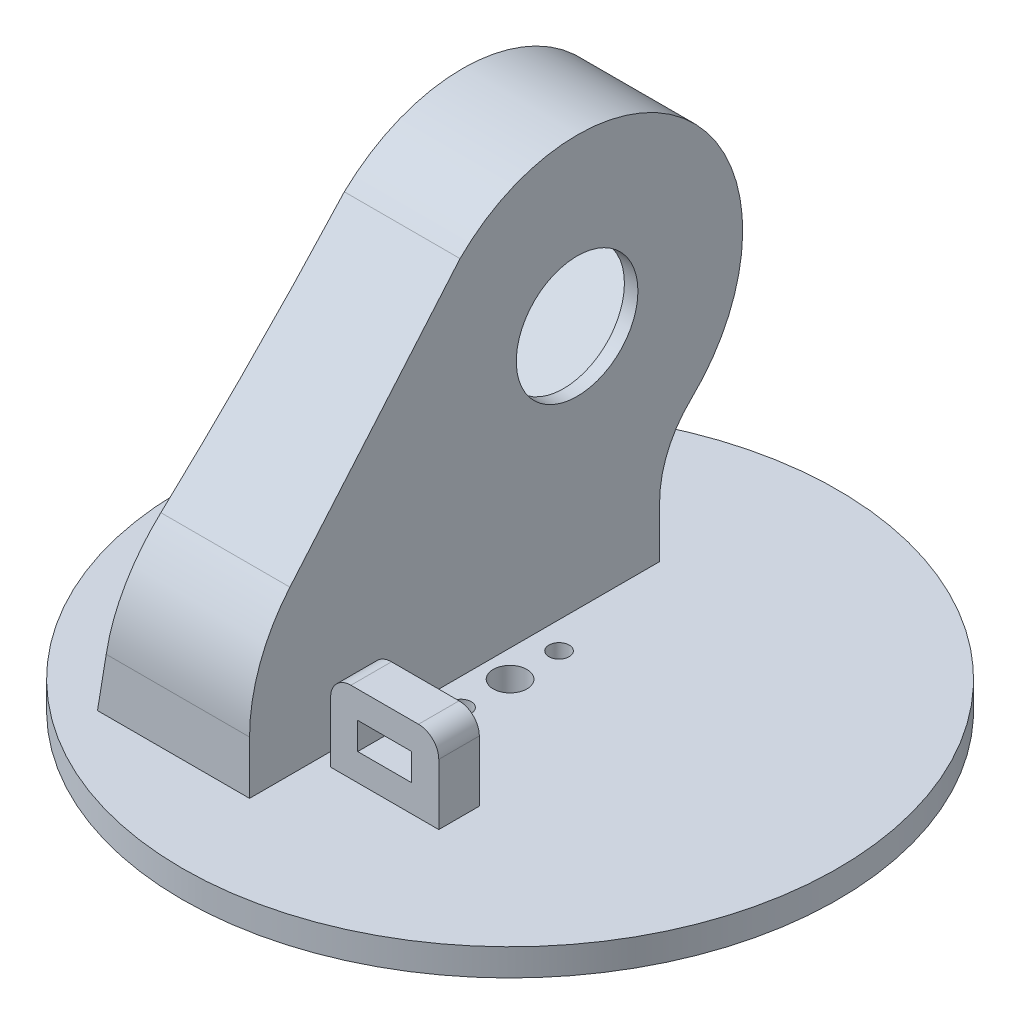
SolidWorks part; units mm, degrees
ref_plane "Front Plane" through (0, 0, 0) normal (0, 0, 1) x (1, 0, 0)
ref_plane "Top Plane" through (0, 0, 0) normal (0, 1, 0) x (1, 0, 0)
ref_plane "Right Plane" through (0, 0, 0) normal (1, 0, 0) x (0, 0, -1)
sketch "Sketch2" plane through (0, 0, 0) normal (0, 1, 0) x (1, 0, 0)
  circle A0 centre (0, 0) radius 48.5
  dimension "D1" = 97
extrude "Boss-Extrude1" add sketch "Sketch2" along normal blind 4
sketch "Sketch4" plane through (0, 0, 0) normal (0, -1, 0) x (1, 0, 0)
  circle A0 centre (0, 7.25) radius 1.5
  circle A1 centre (0, -7.25) radius 1.5
  dimension "D1" = 3
  dimension "D2" = 3
  dimension "D3" = 14.5
  dimension "D4" = 7.25
extrude "Cut-Extrude2" cut sketch "Sketch4" against normal through all
sketch "Sketch5" plane through (0, 0, 0) normal (0, -1, 0) x (1, 0, 0)
  circle A0 centre (0, 0) radius 2.5
  point P3 (0, 0)
  dimension "D1" = 5
extrude "Cut-Extrude3" cut sketch "Sketch5" against normal through all
ref_plane "Plane1" through (-4, 0, 0) normal (1, 0, 0) x (0, 0, -1)
sketch "Sketch7" plane through (-4, 0, 0) normal (1, 0, 0) x (0, 0, -1)
  line L0 (23.1299, 11.6445) -> (23.1299, 4)
  line L5 (48.5, 4) -> (-48.5, 4) construction
  line L6 (-27.2273, 29.5362) -> (-1.2843, 55.4793)
  line L7 (-43.5609, 4) -> (23.1299, 4)
  line L11 (-34.5496, 4) -> (-34.5496, 11.8586)
  arc A4 (28.7298, 24.692) -> (-1.2843, 55.4793) centre (13.9185, 40.2765) ccw
  arc A5 (28.7298, 24.692) -> (23.1299, 11.6445) centre (41.1299, 11.6445) ccw
  arc A6 (-27.2273, 29.5362) -> (-34.5496, 11.8586) centre (-9.5496, 11.8586) ccw
  dimension "D1" = 25
  dimension "D4" = 43
  dimension "D3" = 18
  dimension "D5" = 45
extrude "Boss-Extrude2" add sketch "Sketch7" against normal blind 14
ref_plane "Plane2" through (-6, 0, 0) normal (1, 0, 0) x (0, 0, -1)
sketch "Sketch8" plane through (-6, 0, 0) normal (1, 0, 0) x (0, 0, -1)
  line L0 (-27.2273, 29.5362) -> (-1.2843, 55.4793) construction
  line L1 (-15.2496, 25.9576) -> (13.7417, 54.9489)
  line L2 (-15.2496, 25.9576) -> (-0.4004, 11.1083)
  line L3 (-0.4004, 11.1083) -> (28.591, 40.0997)
  line L4 (13.7417, 54.9489) -> (28.591, 40.0997)
  line L5 (-15.2496, 25.9576) -> (28.591, 40.0997) construction
  line L6 (-0.4004, 11.1083) -> (13.7417, 54.9489) construction
  point P0 (6.6707, 33.0286)
  point P11 (13.9185, 40.2765)
  dimension "D1" = 41
  dimension "D2" = 21
  dimension "D3" = 90
  dimension "D4" = 20.5
  dimension "D5" = 90
  dimension "D6" = 10.25
  dimension "D7" = 10.5
extrude "Cut-Extrude5" cut sketch "Sketch8" against normal up to next
sketch "Sketch9" plane through (-18, 0, 0) normal (-1, 0, 0) x (0, 0, 1)
  line L0 (-13.7417, 54.9489) -> (-28.591, 40.0997) construction
  line L3 (-21.1664, 47.5243) -> (-22.536, 48.894) construction
  circle A0 centre (-20.1057, 53.5347) radius 1.3
  circle A1 centre (-27.1768, 46.4637) radius 1.3
  circle A2 centre (6.7644, 12.5225) radius 1.3
  circle A3 centre (13.8354, 19.5936) radius 1.3
  dimension "D1" = 2.6
  dimension "D5" = 5
  dimension "D6" = 90
  dimension "D2" = 3.5
  dimension "D3" = 2
  dimension "D4" = 2
extrude "Cut-Extrude6" cut sketch "Sketch9" against normal blind 7.5
sketch "Sketch11" plane through (-4, 0, 0) normal (1, 0, 0) x (0, 0, -1)
  circle A0 centre (13.9185, 40.2765) radius 9
  dimension "D1" = 18
extrude "Cut-Extrude9" cut sketch "Sketch11" against normal up to next
sketch "Sketch17" plane through (-18, 0, 0) normal (-1, 0, 0) x (0, 0, 1)
  line L0 (29.3486, 31.6576) -> (3.4056, 57.6006)
  line L1 (-26.1299, 11.6445) -> (-26.1299, 1)
  line L2 (-26.1299, 1) -> (37.5496, 1)
  line L3 (37.5496, 1) -> (37.5496, 11.8586)
  line L4 (27.2273, 29.5362) -> (1.2843, 55.4793)
  line L5 (-23.1299, 11.6445) -> (-23.1299, 4)
  line L6 (-23.1299, 4) -> (34.5496, 4)
  line L7 (34.5496, 4) -> (34.5496, 11.8586)
  line L9 (-23.1299, 11.6445) -> (-23.1299, 4)
  line L10 (-23.1299, 4) -> (34.5496, 4)
  line L11 (34.5496, 4) -> (34.5496, 11.8586)
  line L12 (-26.1299, 4) -> (37.5496, 4)
  line L13 (48.5, 4) -> (-48.5, 4) construction
  line L14 (3.4056, 57.6006) -> (28.5745, 28.0776)
  line L15 (1.2843, 55.4793) -> (26.295, 26.1272)
  line L16 (31.5496, 11.8586) -> (31.5496, 4)
  line L18 (27.2273, 29.5362) -> (1.2843, 55.4793) construction
  arc A0 (3.4056, 57.6006) -> (-30.7965, 22.5174) centre (-13.9185, 40.2765) ccw
  arc A1 (-26.1299, 11.6445) -> (-30.7965, 22.5174) centre (-41.1299, 11.6445) ccw
  arc A2 (37.5496, 11.8586) -> (29.3486, 31.6576) centre (9.5496, 11.8586) ccw
  arc A3 (1.2843, 55.4793) -> (-28.7298, 24.692) centre (-13.9185, 40.2765) ccw
  arc A4 (-23.1299, 11.6445) -> (-28.7298, 24.692) centre (-41.1299, 11.6445) ccw
  arc A5 (34.5496, 11.8586) -> (27.2273, 29.5362) centre (9.5496, 11.8586) ccw
  arc A6 (1.2843, 55.4793) -> (-28.7298, 24.692) centre (-13.9185, 40.2765) ccw
  arc A7 (-23.1299, 11.6445) -> (-28.7298, 24.692) centre (-41.1299, 11.6445) ccw
  arc A8 (34.5496, 11.8586) -> (27.2273, 29.5362) centre (9.5496, 11.8586) ccw
  arc A9 (31.5496, 11.8586) -> (25.106, 27.4149) centre (9.5496, 11.8586) ccw
  line M16 (27.2273, 29.5362) -> (1.2843, 55.4793)
  arc M17 (1.2843, 55.4793) -> (-28.7298, 24.692) centre (-13.9185, 40.2765) ccw
  arc M18 (-28.7298, 24.692) -> (-23.1299, 11.6445) centre (-41.1299, 11.6445) cw
  line M19 (-23.1299, 11.6445) -> (-23.1299, 4)
  line M21 (34.5496, 4) -> (34.5496, 11.8586)
  arc M22 (34.5496, 11.8586) -> (27.2273, 29.5362) centre (9.5496, 11.8586) ccw
  dimension "D1" = 0
  dimension "D2" = 3
  dimension "D3" = 3
extrude "Boss-Extrude7" add sketch "Sketch17" along normal blind 9 and the other way up to surface contours A9 L16 L12 L15 M21 M22 M16 | A1 L1 L12 L14 A0 M19 M18 M17 M16 M22 other way up to face at (-4, 40.2765, -22.9185)
sketch "Sketch25" plane through (-18, 0, 0) normal (-1, 0, 0) x (0, 0, 1)
  line L0 (-23.1299, 11.6445) -> (-23.1299, 4)
  line L1 (48.5, 4) -> (-48.5, 4) construction
  line L2 (-23.1299, 11.6445) -> (-23.1299, 4) construction
  line L3 (1.2843, 55.4793) -> (26.295, 26.1272) construction
  line L4 (31.5496, 4) -> (-23.1299, 4) construction
  line L5 (31.5496, 11.8586) -> (31.5496, 4) construction
  line L6 (31.5496, 4) -> (-23.1299, 4)
  line L7 (31.5496, 11.8586) -> (31.5496, 4)
  line L8 (1.2843, 55.4793) -> (26.295, 26.1272)
  arc A0 (-23.1299, 11.6445) -> (-28.7298, 24.692) centre (-41.1299, 11.6445) ccw construction
  arc A1 (1.2843, 55.4793) -> (-28.7298, 24.692) centre (-13.9185, 40.2765) ccw construction
  arc A2 (-23.1299, 11.6445) -> (-28.7298, 24.692) centre (-41.1299, 11.6445) ccw
  arc A3 (31.5496, 11.8586) -> (26.295, 26.1272) centre (9.5496, 11.8586) ccw construction
  arc A4 (31.5496, 11.8586) -> (26.295, 26.1272) centre (9.5496, 11.8586) ccw
  spline S0 degree 3 poles (-28.7298, 24.692) (-21.9549, 18.2532) (-19.0941, 12.798) (-15.1299, 4) knots 0 0 0 0 1 1 1 1
  spline S1 degree 2 poles (11.7516, 43.195) (26.5513, 25.8264) (25.5496, 4) knots 0 0 0 1 1 1
  dimension "D2" = 8
  dimension "D1" = 6
extrude "Boss-Extrude10" add sketch "Sketch25" along normal up to surface (9 mm away) contours S0 L6 L0 A2 | A4 S1 A2 S0 L8 up to face at (-27, 22.2911, 0.3951)
sketch "Sketch26" plane through (0, 0, 0) normal (0, 0, 1) x (1, 0, 0)
  line L0 (-4, 64.7765) -> (-27, 64.7765) construction
  line L1 (-27, 4) -> (-4, 4) construction
  line L2 (-27, 4) -> (-27, 11.8586) construction
  line L3 (-26, 64.7765) -> (-27, 64.7765)
  line L4 (-27, 64.7765) -> (-27, 4)
  line L5 (-27, 4) -> (-23, 4)
  spline S0 degree 2 poles (-26, 64.7765) (-24.7724, 34.3751) (-23, 4) knots 0 0 0 1 1 1
  dimension "D1" = 1
  dimension "D2" = 4
  dimension "D3" = 2
extrude "Cut-Extrude15" [suppressed] cut sketch "Sketch26" against normal through all both and the other way through all contours L4 L5 S0 L3
sketch "Sketch27" plane through (0, 4, 0) normal (0, 1, 0) x (1, 0, 0)
  line L1 (-2, -18.5496) -> (14, -18.5496)
  line L2 (-2, -18.5496) -> (-2, -24.5496)
  line L3 (-2, -24.5496) -> (14, -24.5496)
  line L4 (14, -18.5496) -> (14, -24.5496)
  line L5 (-27, -34.5496) -> (-4, -34.5496) construction
  line L6 (-4, -34.5496) -> (-4, 26.1299) construction
  dimension "D1" = 10
  dimension "D2" = 6
  dimension "D3" = 16
  dimension "D4" = 2
extrude "Boss-Extrude11" add sketch "Sketch27" along normal blind 12
fillet "Fillet6" radius 3 2 edges at (14, 16, 21.5496) (-2, 16, 21.5496)
sketch "Sketch28" plane through (0, 0, 24.5496) normal (0, 0, 1) x (1, 0, 0)
  line L8 (10, 12) -> (2, 12)
  line L9 (2, 12) -> (2, 8)
  line L10 (2, 8) -> (10, 8)
  line L11 (10, 8) -> (10, 12)
  line L12 (10, 12) -> (2, 12)
  line L13 (2, 12) -> (2, 8)
  line L14 (2, 8) -> (10, 8)
  line L15 (10, 8) -> (10, 12)
  dimension "D1" = 4
extrude "Cut-Extrude16" cut sketch "Sketch28" against normal up to next
sketch "Sketch29" plane through (0, 0, 0) normal (0, 0, 1) x (1, 0, 0)
  line L0 (-4, 64.7765) -> (-27, 64.7765) construction
  line L1 (-27, 4) -> (-4, 4) construction
  line L2 (-21, 64.7765) -> (-27, 64.7765)
  line L3 (-27, 64.7765) -> (-27, 4)
  line L4 (-27, 4) -> (-26.5, 4)
  line L5 (48.5, 4) -> (-48.5, 4) construction
  spline S0 degree 2 poles (-21, 64.7765) (-21.2205, 34.1409) (-26.5, 4) knots 0 0 0 1 1 1
  dimension "D1" = 6
  dimension "D2" = 4
  dimension "D3" = 0.5
  dimension "D4" = 25
extrude "Cut-Extrude17" cut sketch "Sketch29" against normal through all both and the other way through all
